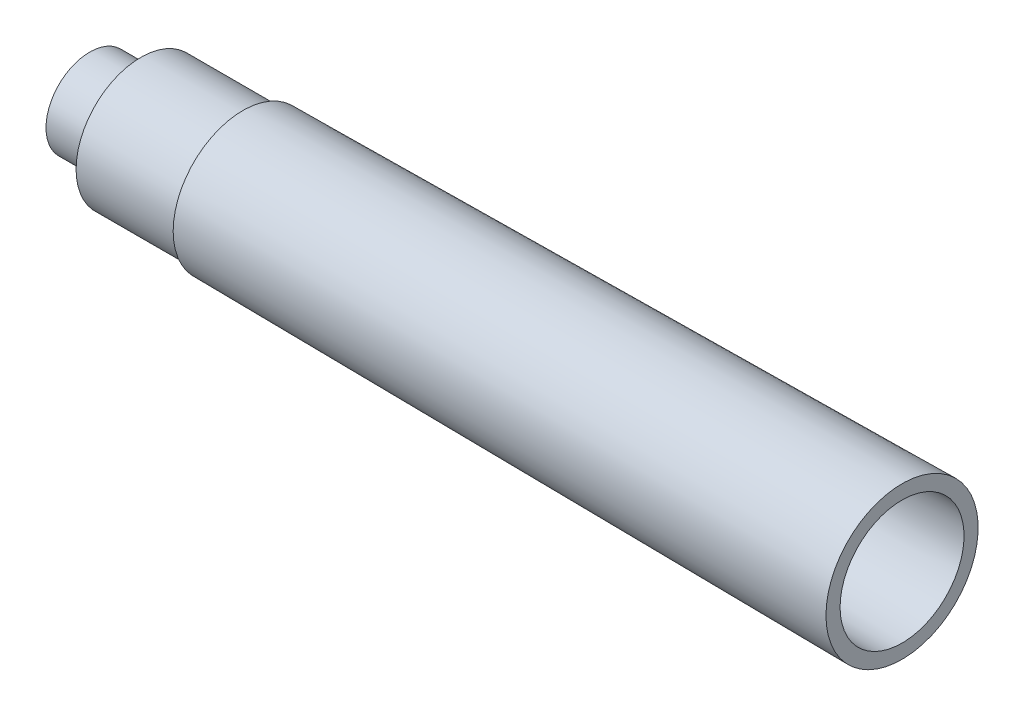
SolidWorks part; units mm, degrees
ref_plane "Plano frontal" through (0, 0, 0) normal (0, 0, 1) x (1, 0, 0)
ref_plane "Plano superior" through (0, 0, 0) normal (0, 1, 0) x (1, 0, 0)
ref_plane "Plano direito" through (0, 0, 0) normal (1, 0, 0) x (0, 0, -1)
sketch "Esboço1" plane through (0, 0, 0) normal (0, 0, 1) x (1, 0, 0)
  line L0 (0.8839, 3.5878) -> (14.6798, 3.5878) construction
  line L1 (0.466, 5.7562) -> (2.566, 5.7562)
  line L2 (2.566, 5.7562) -> (3.0004, 6.7978)
  line L3 (3.0004, 6.7978) -> (8.066, 6.7978)
  line L4 (8.066, 6.7978) -> (8.066, 7.0478)
  line L5 (8.066, 7.0478) -> (40.766, 7.3628)
  line L6 (0.466, 5.7562) -> (0.466, 5.4062)
  line L7 (0.466, 5.4062) -> (2.2466, 5.4062)
  line L8 (2.2466, 5.4062) -> (2.2466, 5.1128)
  line L9 (2.2466, 5.1128) -> (0.8839, 5.1128)
  line L10 (0.8839, 5.1128) -> (0.8839, 4.7628)
  line L11 (0.8839, 4.7628) -> (2.2466, 4.7628)
  line L12 (2.2466, 4.7628) -> (2.9101, 4.7628)
  line L13 (2.9101, 4.7628) -> (3.4669, 6.0978)
  line L14 (3.4669, 6.0978) -> (7.3432, 6.0978)
  line L15 (7.3432, 6.0978) -> (8.766, 6.0978)
  line L16 (8.766, 6.0978) -> (8.766, 6.3478)
  line L17 (8.766, 6.3478) -> (40.766, 6.6628)
  line L18 (40.766, 6.6628) -> (40.766, 7.0478)
  line L20 (40.766, 7.3628) -> (40.766, 7.0478)
  dimension "D1" = 40.3
  dimension "D2" = 2.1
  dimension "D3" = 5.5
  dimension "D4" = 32.7
  dimension "D5" = 0.35
  dimension "D6" = 0.35
  dimension "D7" = 0.9934
  dimension "D8" = 0.7
  dimension "D9" = 0.7
  dimension "D10" = 0.7
  dimension "D11" = 0.7
  dimension "D12" = 1.175
  dimension "D13" = 3.21
  dimension "D14" = 6.92
  dimension "D15" = 7.55
revolve "Revolução1" add sketch "Esboço1" angle 360 about L0
